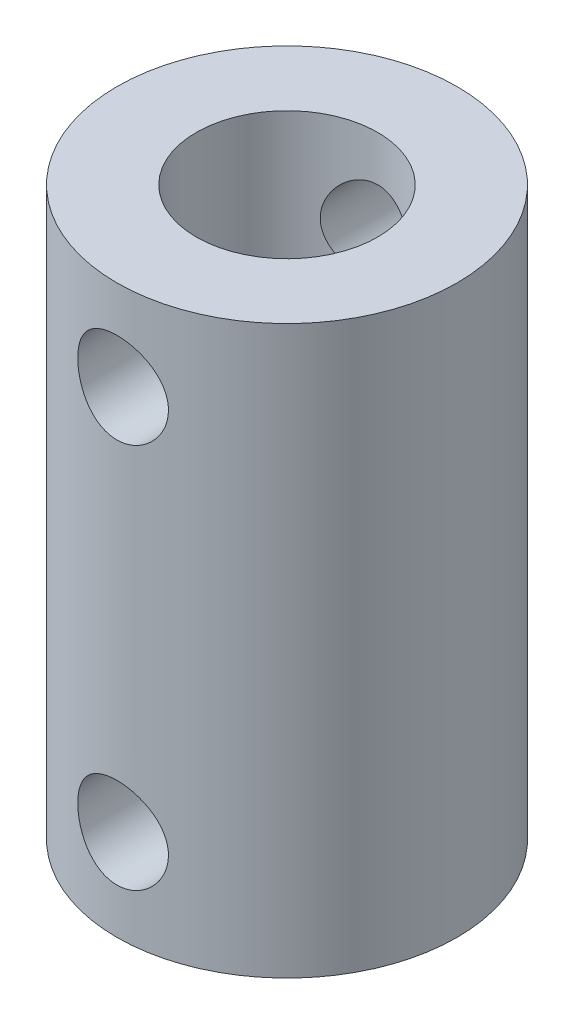
SolidWorks part; units mm, degrees
ref_plane "Front Plane" through (0, 0, 0) normal (0, 0, 1) x (1, 0, 0)
ref_plane "Top Plane" through (0, 0, 0) normal (0, 1, 0) x (1, 0, 0)
ref_plane "Right Plane" through (0, 0, 0) normal (1, 0, 0) x (0, 0, -1)
sketch "Sketch1" plane through (0, 0, 0) normal (0, 1, 0) x (1, 0, 0)
  circle A0 centre (0, 0) radius 7.5
  circle A1 centre (0, 0) radius 4
  dimension "D1" = 15
  dimension "D2" = 8
extrude "Boss-Extrude1" add sketch "Sketch1" along normal blind 14
sketch "Sketch2" plane through (0, 0, 0) normal (0, -1, 0) x (1, 0, 0)
  circle A0 centre (0, 0) radius 7.5 construction
  circle A1 centre (0, 0) radius 7.5
  circle A2 centre (0, 0) radius 2.5
  dimension "D1" = 5
extrude "Boss-Extrude2" add sketch "Sketch2" along normal blind 11
sketch "Sketch3" plane through (0, 0, 0) normal (0, 0, 1) x (1, 0, 0)
  line L0 (7.5, 14) -> (-7.5, 14) construction
  line L1 (0, 0) -> (5.2403, 0) construction
  line L2 (-7.5, -11) -> (7.5, -11) construction
  circle A0 centre (0, 10) radius 2
  circle A1 centre (0, -7) radius 2
  point P11 (0, 0)
  point P12 (0, 0)
  dimension "D1" = 4
  dimension "D2" = 4
  dimension "D3" = 4
  dimension "D4" = 4
extrude "Cut-Extrude1" cut sketch "Sketch3" against normal through all both and the other way through all
